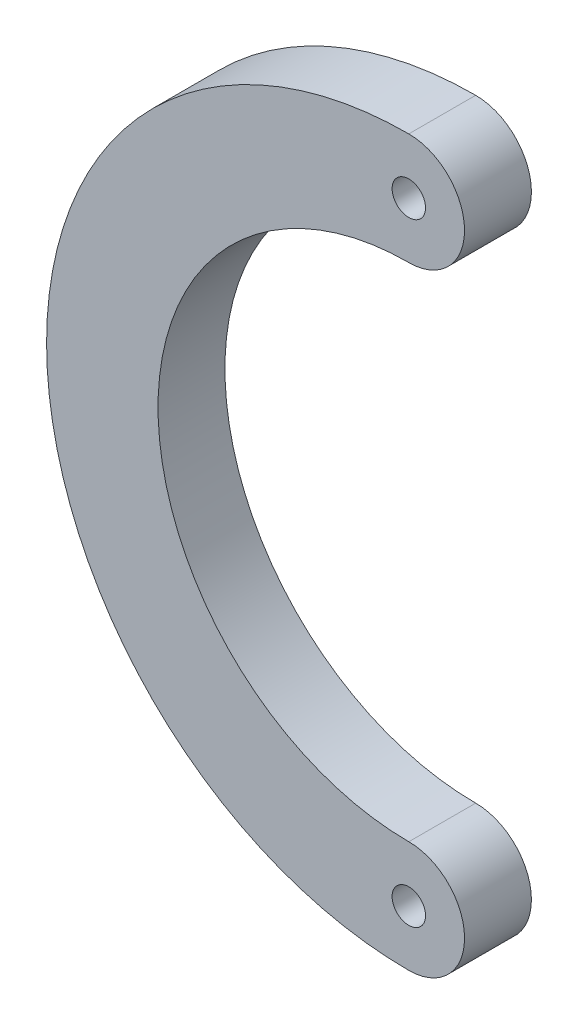
SolidWorks part; units mm, degrees
ref_plane "Front Plane" through (0, 0, 0) normal (0, 0, 1) x (1, 0, 0)
ref_plane "Top Plane" through (0, 0, 0) normal (0, 1, 0) x (1, 0, 0)
ref_plane "Right Plane" through (0, 0, 0) normal (1, 0, 0) x (0, 0, -1)
sketch "Sketch1" plane through (0, 0, 0) normal (0, 0, 1) x (1, 0, 0)
  arc A0 (0, 32.5) -> (0, -32.5) centre (0, 0) ccw
  arc A1 (0, 22.5) -> (0, -22.5) centre (0, 0) ccw
  arc A2 (0, 22.5) -> (0, 32.5) centre (0, 27.5) ccw
  arc A3 (0, -32.5) -> (0, -22.5) centre (0, -27.5) ccw
  dimension "D1" = 10
  dimension "D2" = 55
extrude "Boss-Extrude1" add sketch "Sketch1" along normal blind 6
hole_wizard "Ø3.0mm Dowel Hole1" positions "Sketch2" profile "Sketch3" hole size "Ø3.0" standard "ANSI Metric" end condition through all
sketch "Sketch2" plane through (0, 0, 6) normal (0, 0, 1) x (1, 0, 0)
  arc A0 (0, -32.5) -> (0, -22.5) centre (0, -27.5) ccw construction
  arc A1 (0, 22.5) -> (0, 32.5) centre (0, 27.5) ccw construction
  point P0 (0, 27.5)
  point P2 (0, -27.5)
sketch "Sketch3" plane through (0, 27.5, 6) normal (1, 0, 0) x (0, -1, 0)
  line L0 (0, 0) -> (0, 6)
  line L1 (0, 6) -> (1.5, 6)
  line L2 (1.5, 6) -> (1.5, 0)
  line L5 (1.5, 0) -> (0, 0)
  line L11 (0, -6.35) -> (0, 107.95) construction
  dimension "Thru Hole Dia." = 3
  dimension "Thru Hole Depth" = 6
